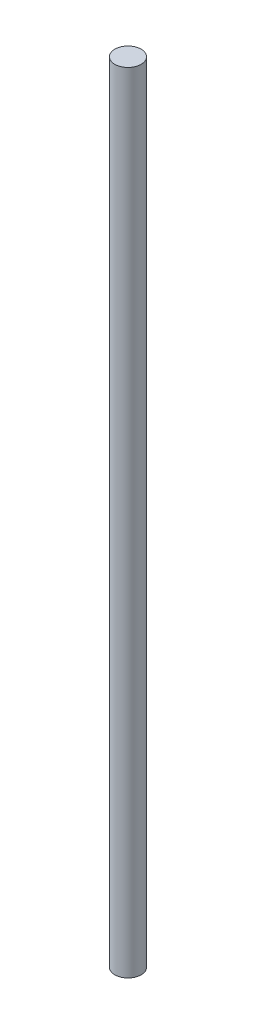
SolidWorks part; units mm, degrees
material "3.1645 (EN-AW 2030)"
ref_plane "前视基准面" through (0, 0, 0) normal (0, 0, 1) x (1, 0, 0)
ref_plane "上视基准面" through (0, 0, 0) normal (0, 1, 0) x (1, 0, 0)
ref_plane "右视基准面" through (0, 0, 0) normal (1, 0, 0) x (0, 0, -1)
sketch "草图1" plane through (0, 0, 0) normal (0, 1, 0) x (1, 0, 0)
  circle A0 centre (0, 0) radius 2
  dimension "D1" = 4
extrude "凸台-拉伸1" add sketch "草图1" along normal blind 120
